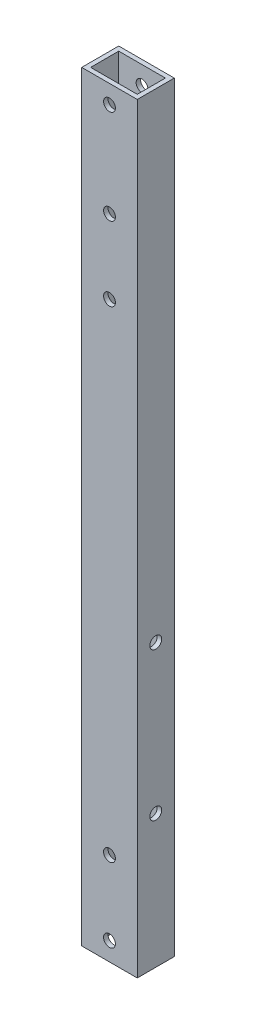
SolidWorks part; units mm, degrees
ref_plane "正面" through (0, 0, 0) normal (0, 0, 1) x (1, 0, 0)
ref_plane "平面" through (0, 0, 0) normal (0, 1, 0) x (1, 0, 0)
ref_plane "右側面" through (0, 0, 0) normal (1, 0, 0) x (0, 0, -1)
sketch "ｽｹｯﾁ1" plane through (0, 0, 0) normal (0, 1, 0) x (1, 0, 0)
  line L0 (-6.3, 3.8) -> (6.3, 3.8)
  line L1 (-7.5, 5) -> (7.5, 5)
  line L2 (-7.5, 5) -> (-7.5, -5)
  line L3 (-7.5, -5) -> (7.5, -5)
  line L4 (7.5, 5) -> (7.5, -5)
  line L5 (-7.5, 5) -> (7.5, -5) construction
  line L6 (-7.5, -5) -> (7.5, 5) construction
  line L7 (6.3, 3.8) -> (6.3, -3.8)
  line L8 (-6.3, -3.8) -> (6.3, -3.8)
  line L9 (-6.3, 3.8) -> (-6.3, -3.8)
  point P0 (0, 0)
  dimension "D1" = 15
  dimension "D2" = 10
  dimension "D3" = 1.2
extrude "ﾎﾞｽ - 押し出し1" add sketch "ｽｹｯﾁ1" along normal mid plane 220
sketch "ｽｹｯﾁ2" plane through (0, 0, -5) normal (0, 0, -1) x (-1, 0, 0)
  line L0 (0, -110) -> (0, -85) construction
  line L1 (-7.5, -110) -> (7.5, -110) construction
  circle A0 centre (0, -85) radius 1.6
  circle A1 centre (0, -105) radius 1.6
  dimension "D2" = 3.2
  dimension "D3" = 3.2
  dimension "D1" = 25
  dimension "D4" = 20
extrude "ｶｯﾄ - 押し出し1" cut sketch "ｽｹｯﾁ2" against normal blind 100
sketch "ｽｹｯﾁ3" plane through (-7.5, 0, 0) normal (-1, 0, 0) x (0, 0, 1)
  line L0 (0, -110) -> (0, 0) construction
  line L1 (-5, -110) -> (5, -110) construction
  circle A0 centre (0, -74) radius 1.6
  circle A1 centre (0, -34) radius 1.6
  dimension "D1" = 3.2
  dimension "D2" = 3.2
extrude "ｶｯﾄ - 押し出し2" cut sketch "ｽｹｯﾁ3" against normal blind 15
sketch "ｽｹｯﾁ4" plane through (0, 0, -5) normal (0, 0, -1) x (-1, 0, 0)
  circle A0 centre (0, 45) radius 1.6
  circle A1 centre (0, 65) radius 1.6
  dimension "D1" = 3.2
  dimension "D2" = 3.2
  dimension "D3" = 20
  dimension "D4" = 65
extrude "ｶｯﾄ - 押し出し3" cut sketch "ｽｹｯﾁ4" against normal blind 10
sketch "ｽｹｯﾁ5" plane through (0, 110, 0) normal (0, 1, 0) x (1, 0, 0)
  line L4 (7.5, -5) -> (7.5, 5)
  line L5 (7.5, 5) -> (-7.5, 5)
  line L6 (-7.5, 5) -> (-7.5, -5)
  line L7 (-7.5, -5) -> (7.5, -5)
  line L8 (7.5, -5) -> (7.5, 5)
  line L9 (7.5, 5) -> (-7.5, 5)
  line L10 (-7.5, 5) -> (-7.5, -5)
  line L11 (-7.5, -5) -> (7.5, -5)
  dimension "D1" = 0
extrude "ｶｯﾄ - 押し出し4" cut sketch "ｽｹｯﾁ5" against normal blind 14.5
sketch "ｽｹｯﾁ6" plane through (0, 0, -5) normal (0, 0, -1) x (-1, 0, 0)
  line L0 (0, 95.5) -> (0, 90.5) construction
  line L1 (-7.5, 95.5) -> (7.5, 95.5) construction
  circle A0 centre (0, 90.5) radius 1.6
  dimension "D2" = 3.2
  dimension "D1" = 5
extrude "ｶｯﾄ - 押し出し5" cut sketch "ｽｹｯﾁ6" against normal blind 15
